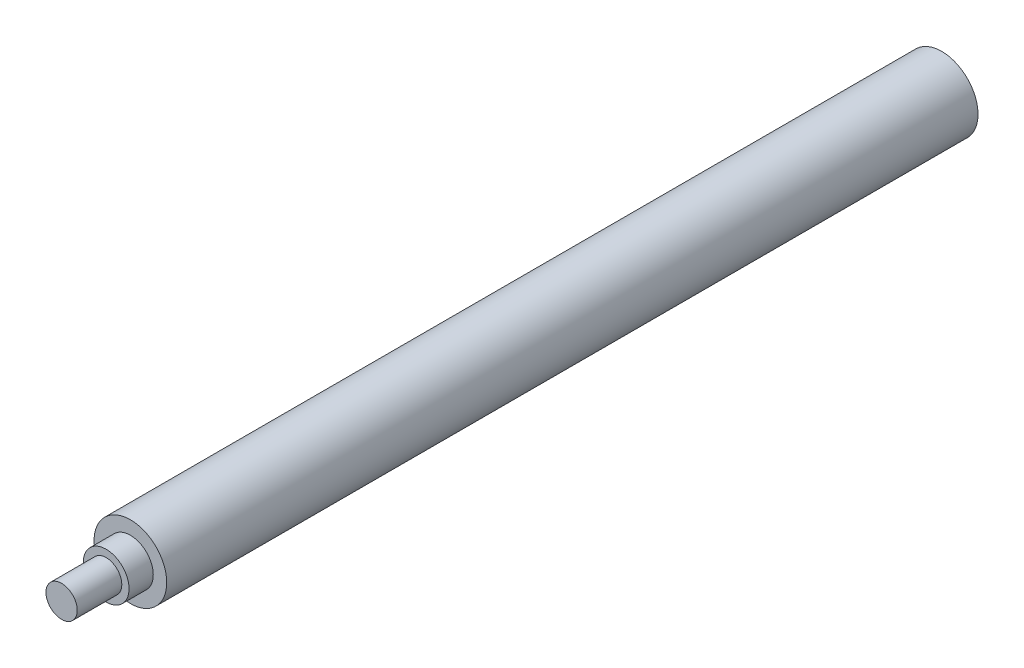
SolidWorks part; units mm, degrees
ref_plane "Front Plane" through (0, 0, 0) normal (0, 0, 1) x (1, 0, 0)
ref_plane "Top Plane" through (0, 0, 0) normal (0, 1, 0) x (1, 0, 0)
ref_plane "Right Plane" through (0, 0, 0) normal (1, 0, 0) x (0, 0, -1)
sketch "Sketch1" plane through (0, 0, 0) normal (0, 1, 0) x (1, 0, 0)
  line L0 (4.7625, 104.775) -> (-4.7625, 104.775) construction
  line L1 (4.915, -10.6045) -> (-4.915, -10.6045) construction
  line L2 (2.05, -1.5875) -> (2.05, -10.6045) construction
  line L3 (4.915, -4.7625) -> (-4.915, -4.7625) construction
  line L4 (3, -1.5875) -> (3, -4.7625) construction
  line L5 (4.7625, -1.5875) -> (-4.7625, -1.5875) construction
  line L6 (0, -1.5875) -> (0, 104.775) construction
  line L7 (4.7625, -1.5875) -> (4.7625, 104.775) construction
  line L8 (4.7625, 104.775) -> (0, 104.775)
  line L9 (2.05, -10.6045) -> (0, -10.6045)
  line L10 (2.05, -4.7625) -> (2.05, -10.6045)
  line L11 (3, -4.7625) -> (2.05, -4.7625)
  line L12 (3, -1.5875) -> (3, -4.7625)
  line L13 (4.7625, -1.5875) -> (3, -1.5875)
  line L14 (0, -10.6045) -> (0, 104.775)
  line L15 (4.7625, -1.5875) -> (4.7625, 104.775)
revolve "Revolve1" add sketch "Sketch1" angle 360 about L14
